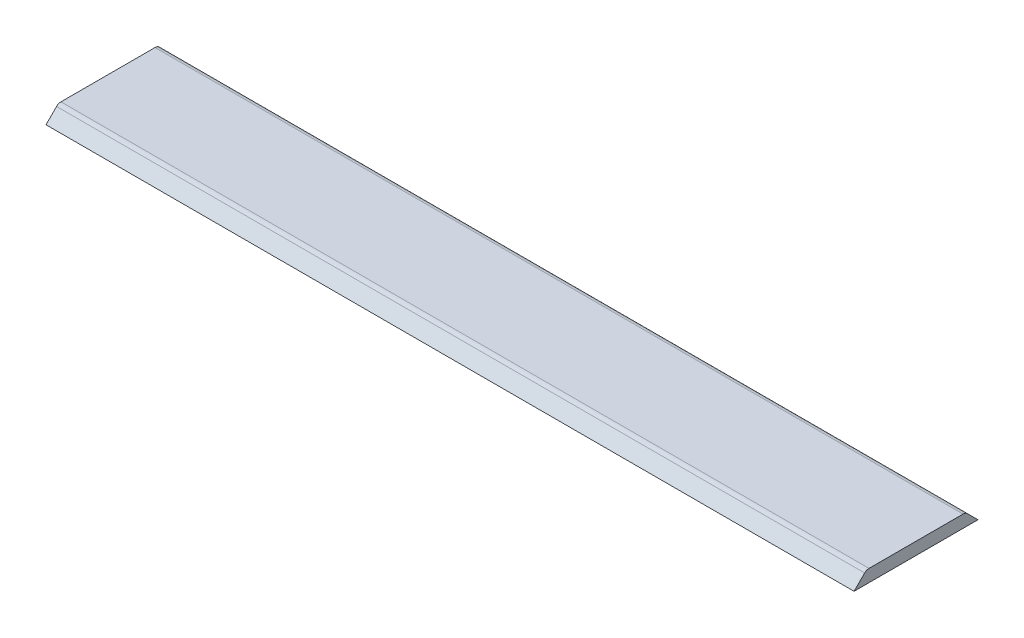
SolidWorks part; units mm, degrees
ref_plane "前视基准面" through (0, 0, 0) normal (0, 0, 1) x (1, 0, 0)
ref_plane "上视基准面" through (0, 0, 0) normal (0, 1, 0) x (1, 0, 0)
ref_plane "右视基准面" through (0, 0, 0) normal (1, 0, 0) x (0, 0, -1)
sketch "草图1" plane through (0, 0, 0) normal (1, 0, 0) x (0, 0, -1)
  line L1 (0, 0) -> (5000, 0)
  line L2 (0, 0) -> (500, 500)
  line L3 (500, 500) -> (4500, 500)
  line L4 (5000, 0) -> (4500, 500)
  dimension "D1" = 4000
  dimension "D2" = 5000
  dimension "D3" = 500
  dimension "D4" = 500
extrude "凸台-拉伸1" add sketch "草图1" along normal blind 32600
fillet "圆角1" radius 250 2 edges at (16300, 500, -4500) (16300, 500, -500)
